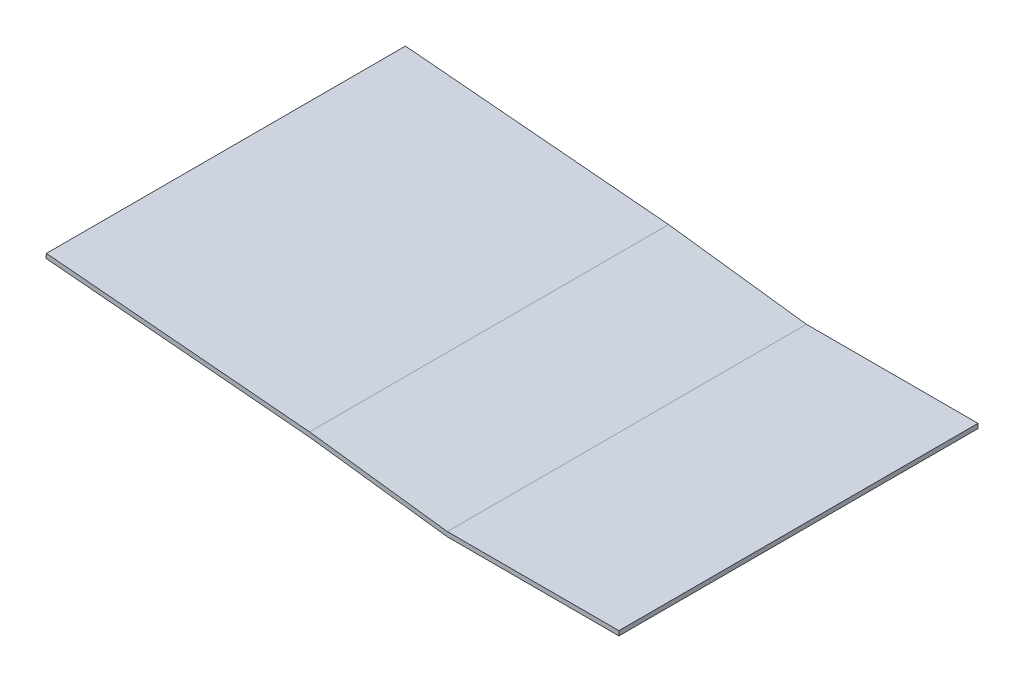
SolidWorks part; units mm, degrees
material "ASTM A500 Grade B Steel"
ref_plane "Front Plane" through (0, 0, 0) normal (0, 0, 1) x (1, 0, 0)
ref_plane "Top Plane" through (0, 0, 0) normal (0, 1, 0) x (1, 0, 0)
ref_plane "Right Plane" through (0, 0, 0) normal (1, 0, 0) x (0, 0, -1)
sketch "Sketch1" plane through (0, 0, 0) normal (0, 0, 1) x (1, 0, 0)
  line L0 (-4531.5317, -124.9847) -> (-4531.8084, -128.1476)
  line L2 (-4252.391, -153.1622) -> (-4252.391, -156.3372)
  line L3 (-4252.391, -156.3372) -> (-4132.9267, -156.3372)
  line L5 (-4132.9267, -156.3372) -> (-4132.9267, -153.1622)
  line L7 (-4132.9267, -153.1622) -> (-4252.391, -153.1622)
  line L8 (-4252.391, -153.1622) -> (-4348.3248, -141.0132)
  line L9 (-4348.3248, -141.0132) -> (-4531.5317, -124.9847)
  line L10 (-4531.8084, -128.1476) -> (-4348.1066, -144.2194)
  line L11 (-4348.1066, -144.2194) -> (-4252.391, -156.3372)
  point P0 (-4200, -153.1622)
  dimension "D1" = 3.175
  dimension "D2" = 3.175
extrude "Boss-Extrude1" add sketch "Sketch1" against normal blind 250 contours L10 L11 L2 L8 L9 L0 | L5 L7 L2 L3
